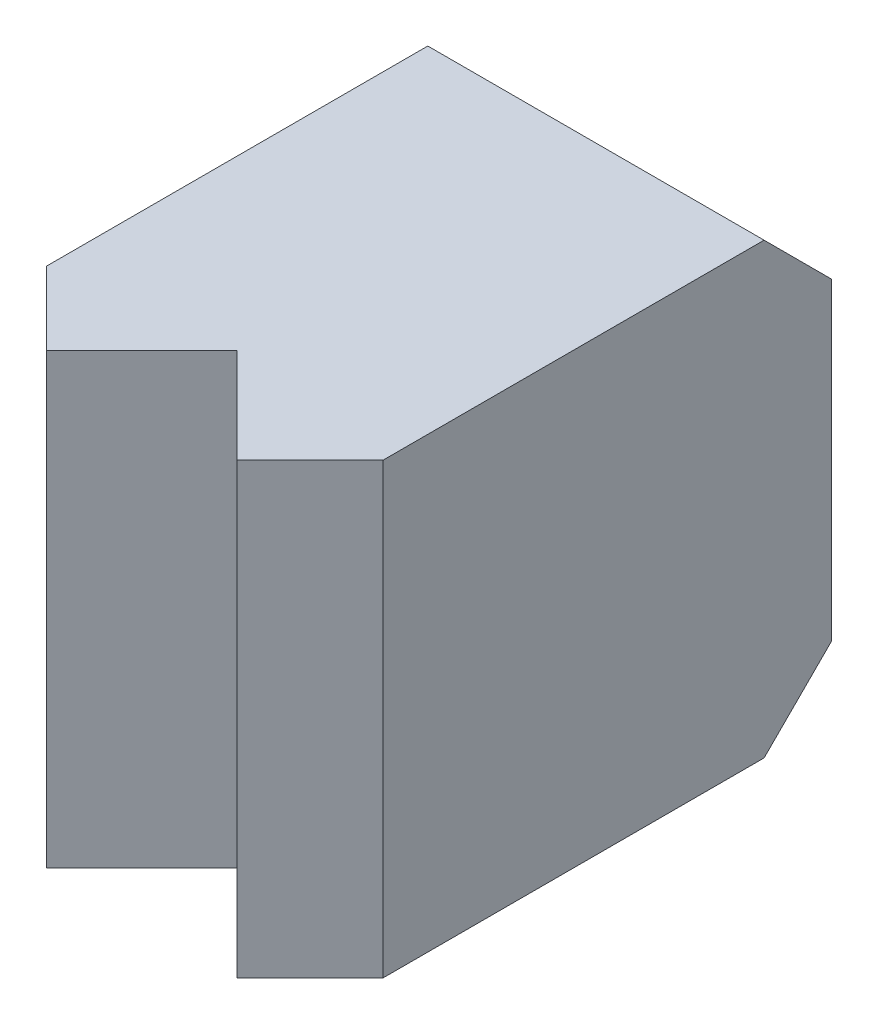
SolidWorks part; units mm, degrees
ref_plane "前基準面" through (0, 0, 0) normal (0, 0, 1) x (1, 0, 0)
ref_plane "上基準面" through (0, 0, 0) normal (0, 1, 0) x (1, 0, 0)
ref_plane "右基準面" through (0, 0, 0) normal (1, 0, 0) x (0, 0, -1)
sketch "草圖1" plane through (0, 0, 0) normal (0, 1, 0) x (1, 0, 0)
  line L0 (0, 0) -> (0, -20)
  line L1 (0, 0) -> (15, 0)
  line L3 (15, 0) -> (15, -20)
  line L4 (3.2574, -23.2574) -> (7.5, -19.0147)
  line L5 (7.5, -19.0147) -> (11.7426, -23.2574)
  line L7 (11.7426, -23.2574) -> (15, -20)
  line L8 (3.2574, -23.2574) -> (0, -20)
  line L9 (0, -20) -> (15, -20) construction
  dimension "D1" = 6
  dimension "D2" = 20
  dimension "D3" = 15
extrude "填料-伸長1" add sketch "草圖1" along normal blind 20
sketch "草圖2" plane through (0, 0, 0) normal (0, 0, -1) x (-1, 0, 0)
  line L0 (-15, 0) -> (0, 20) construction
  circle A0 centre (-7.5, 10) radius 5
  dimension "D1" = 10
extrude "除料-伸長1" cut sketch "草圖2" against normal blind 18
chamfer "導角1" distance 3 angle 45 2 edges at (7.5, 0, 0) (7.5, 20, 0)
